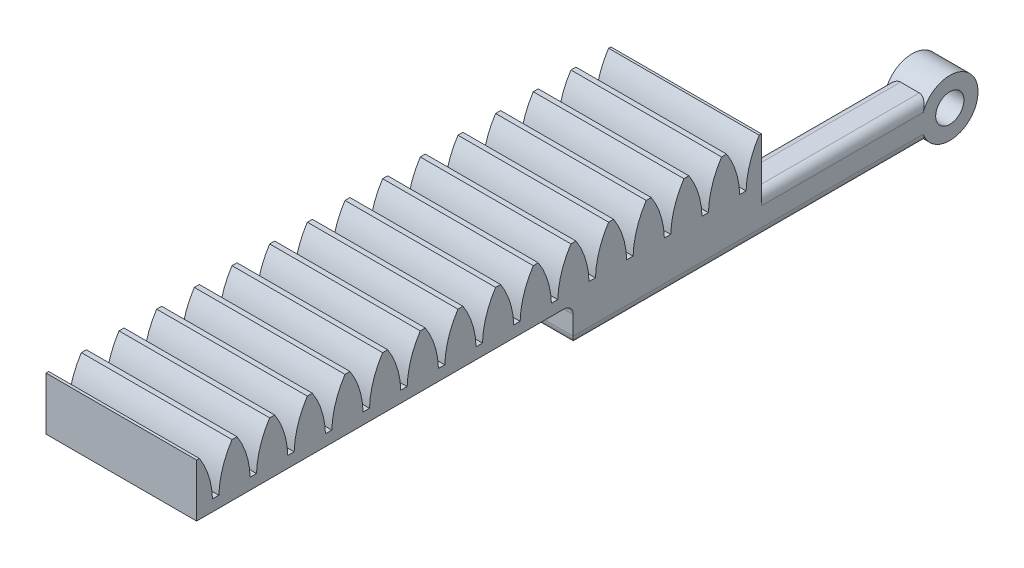
SolidWorks part; units mm, degrees
ref_plane "Front Plane" through (0, 0, 0) normal (0, 0, 1) x (1, 0, 0)
ref_plane "Top Plane" through (0, 0, 0) normal (0, 1, 0) x (1, 0, 0)
ref_plane "Right Plane" through (0, 0, 0) normal (1, 0, 0) x (0, 0, -1)
sketch "Sketch1" plane through (0, 0, 0) normal (0, 0, 1) x (1, 0, 0)
  line L1 (-1, -1) -> (1, -1)
  line L2 (-1, -1) -> (-1, 1)
  line L3 (-1, 1) -> (1, 1)
  line L4 (1, -1) -> (1, 1)
  line L5 (-1, -1) -> (1, 1) construction
  line L6 (-1, 1) -> (1, -1) construction
  point P0 (0, 0)
  dimension "D1" = 2
  dimension "D2" = 2
extrude "Boss-Extrude1" add sketch "Sketch1" along normal blind 20
sketch "Sketch2" plane through (0, 0, 0) normal (1, 0, 0) x (0, 0, -1)
  circle A0 centre (0, 0) radius 1.5
  dimension "D1" = 3
extrude "Boss-Extrude2" add sketch "Sketch2" along normal up to surface and the other way up to surface up to face at (1, 0, 10) other way up to face at (-1, 0, 10)
sketch "Sketch3" plane through (0, 0, 0) normal (1, 0, 0) x (0, 0, -1)
  circle A0 centre (0, 0) radius 0.75
  dimension "D1" = 1.5
extrude "Cut-Extrude1" cut sketch "Sketch3" against normal through all both and the other way through all
sketch "Sketch4" plane through (0, 1, 0) normal (0, 1, 0) x (1, 0, 0)
  line L6 (1, -10) -> (-7, -10)
  line L7 (1, -10) -> (1, -40)
  line L8 (1, -40) -> (-7, -40)
  line L9 (-7, -10) -> (-7, -40)
  line L10 (1, -20) -> (-1, -20) construction
  line L11 (1, -20) -> (1, -1.118) construction
  dimension "D1" = 30
  dimension "D2" = 10
  dimension "D3" = 8
sketch "Sketch8" plane through (0, 0, 0) normal (1, 0, 0) x (0, 0, -1)
  line L0 (-36.9897, -3.34) -> (-36.9897, 3.81) construction
  circle A0 centre (-36.9897, -3.34) radius 6.5
  circle A1 centre (-36.9897, -3.34) radius 7.15
  circle A2 centre (-36.9897, -3.34) radius 4.94
  point P4 (-36.9897, 3.81)
  point P5 (-36.9897, 1.6)
  dimension "D2" = 13
  dimension "D3" = 14.3
  dimension "D1" = 1.56
  dimension "D4" = 0.6
extrude "Boss-Extrude4" add sketch "Sketch4" along normal up to vertex (2.81 mm away) up to point (0, 3.81, 36.9897)
sketch "Sketch9" plane through (0, 0, 0) normal (1, 0, 0) x (0, 0, -1)
  line L0 (-36.9897, -3.34) -> (-36.9897, 3.81) construction
  line L1 (-36.9897, -3.34) -> (-36.9897, 3.81) construction
  line L2 (-37.1582, 1.5971) -> (-36.9897, -3.34) construction
  line L3 (-36.9897, 1.9385) -> (-38.0506, 4.438) construction
  line L4 (-37.4996, 3.14) -> (-36.4797, 3.14) construction
  line L5 (-36.9897, -3.34) -> (-35.8712, 3.722) construction
  line L6 (-36.4797, 3.14) -> (-35.4723, 2.9804) construction
  arc A0 (-38.3153, 4.3973) -> (-37.1582, 1.5971) centre (-41.4822, 1.4495) cw
  circle A1 centre (-36.9897, -3.34) radius 4.94 construction
  arc A2 (-36.8211, 1.5971) -> (-37.1582, 1.5971) centre (-36.9897, -3.34) ccw
  arc A3 (-35.664, 4.3973) -> (-36.8211, 1.5971) centre (-32.4972, 1.4495) ccw
  circle A4 centre (-36.9897, -3.34) radius 7.15 construction
  circle A6 centre (-36.9897, -3.34) radius 6.5 construction
  circle A7 centre (-36.9897, -3.34) radius 7.85
  arc A8 (-35.664, 4.3973) -> (-38.3153, 4.3973) centre (-36.9897, -3.34) ccw
  dimension "D2" = 23
  dimension "D3" = 9
  dimension "D1" = 0.7
extrude "Cut-Extrude3" cut sketch "Sketch9" against normal through all both and the other way through all
pattern_linear "LPattern1" count 14 spacing 2 along (0, 0, -1) count 2 spacing 2 along (0, 0, 1) of "Cut-Extrude3"
fillet "Fillet2" radius 0.5 6 edges at (-1, -1, 10.559) (1, -1, 10.559) (1, 1, 5.559) (-1, 1, 5.559) (0, -1, 20) (0, 1, 20)
equation "\"Teeth\"= 20"
equation "\"PitchDiameter\"= 13"
equation "\"Module\"= \"PitchDiameter\" / \"Teeth\""
equation "\"D1@Sketch8\"= \"Module\" * ( IIF ( \"Module\" = > 1.25 , 2.25 , 2.4 ) )"
equation "\"D2@Sketch8\"=\"PitchDiameter\""
equation "\"D3@Sketch8\"= ( \"Teeth\" + 2) * \"Module\""
equation "\"D3@Sketch9\"= 180 / \"Teeth\""
